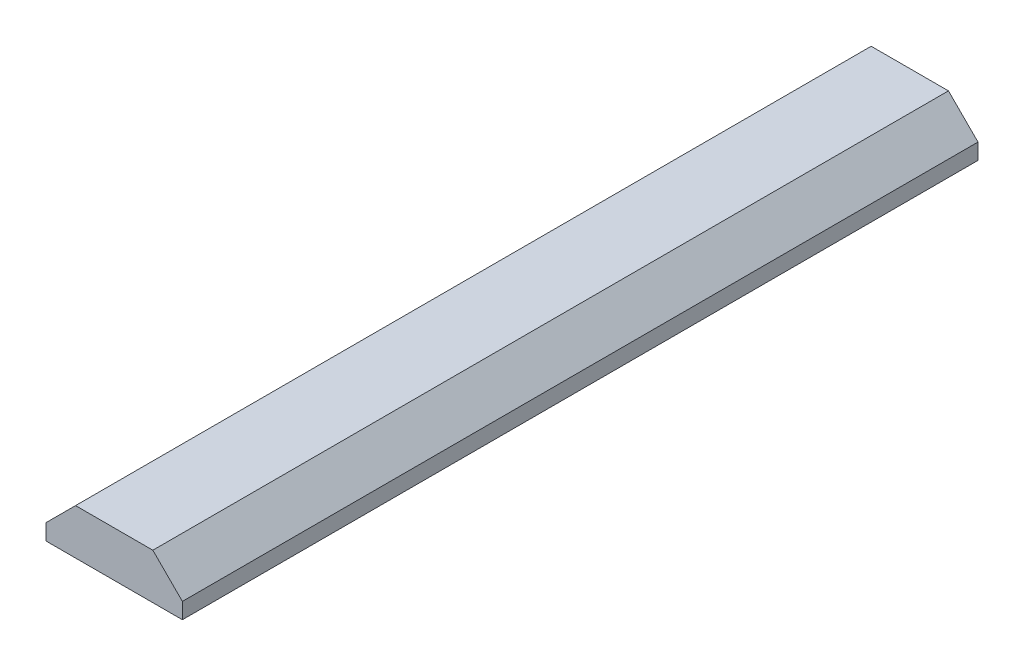
SolidWorks part; units mm, degrees
ref_plane "Ebene vorne" through (0, 0, 0) normal (0, 0, 1) x (1, 0, 0)
ref_plane "Ebene oben" through (0, 0, 0) normal (0, 1, 0) x (1, 0, 0)
ref_plane "Ebene rechts" through (0, 0, 0) normal (1, 0, 0) x (0, 0, -1)
sketch "Skizze1" plane through (0, 0, 0) normal (0, 0, 1) x (1, 0, 0)
  line L0 (0, 0) -> (0, 23680.6173) construction
  line L1 (3.4, 1.8089) -> (-3.4, 1.8089)
  line L2 (-3.4, 1.8089) -> (-6, -0.7911)
  line L3 (-6, -0.7911) -> (-6, -2.1911)
  line L4 (-6, -2.1911) -> (6, -2.1911)
  line L5 (6, -0.7911) -> (6, -2.1911)
  line L6 (3.4, 1.8089) -> (6, -0.7911)
  point P9 (0, -2.1911)
  point P11 (0, 1.8089)
  dimension "D1" = 3.4
  dimension "D2" = 6
  dimension "D3" = 4
  dimension "D4" = 135
extrude "Aufsatz-Linear austragen1" add sketch "Skizze1" along normal blind 70 contours L1 L2 L3 L4 L5 L6
